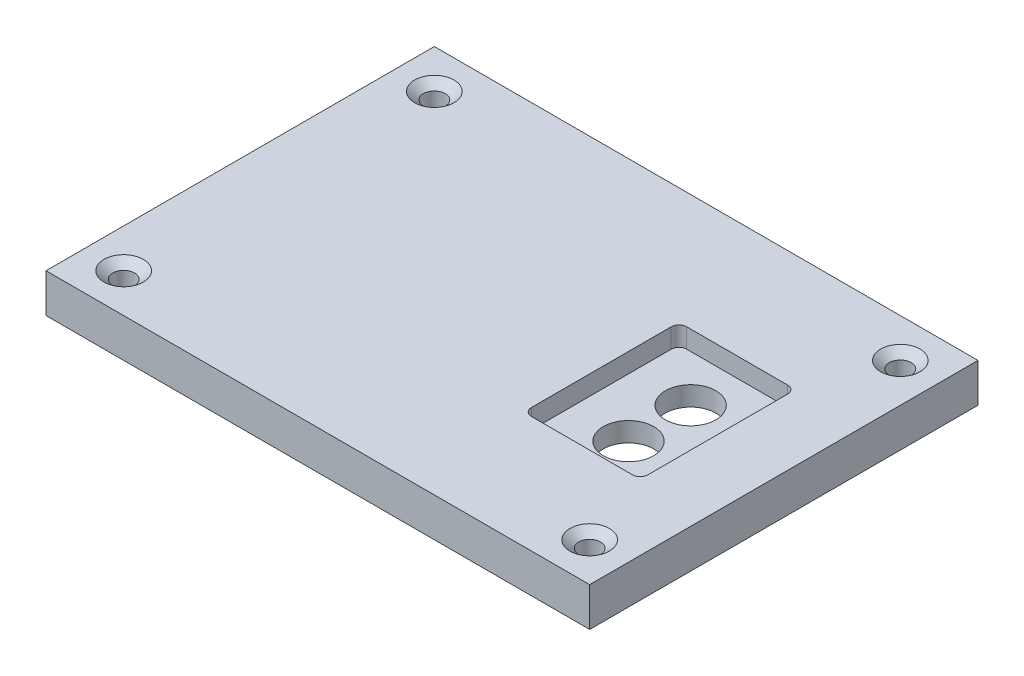
SolidWorks part; units mm, degrees
ref_plane "Front Plane" through (0, 0, 0) normal (0, 0, 1) x (1, 0, 0)
ref_plane "Top Plane" through (0, 0, 0) normal (0, 1, 0) x (1, 0, 0)
ref_plane "Right Plane" through (0, 0, 0) normal (1, 0, 0) x (0, 0, -1)
sketch "Sketch1" plane through (0, 0, 0) normal (0, 1, 0) x (1, 0, 0)
  line L1 (-88.9, -63.5) -> (88.9, -63.5)
  line L2 (-88.9, -63.5) -> (-88.9, 63.5)
  line L3 (-88.9, 63.5) -> (88.9, 63.5)
  line L4 (88.9, -63.5) -> (88.9, 63.5)
  line L5 (-88.9, -63.5) -> (88.9, 63.5) construction
  line L6 (-88.9, 63.5) -> (88.9, -63.5) construction
  point P0 (0, 0)
  dimension "D1" = 177.8
  dimension "D2" = 127
extrude "Boss-Extrude1" add sketch "Sketch1" along normal blind 12.7
sketch "Sketch2" plane through (0, 12.7, 0) normal (0, 1, 0) x (1, 0, 0)
  line L0 (-88.9, -63.5) -> (88.9, -63.5) construction
  line L1 (-88.9, 63.5) -> (-88.9, -63.5) construction
  line L2 (88.9, -63.5) -> (88.9, 63.5) construction
  line L3 (88.9, 63.5) -> (-88.9, 63.5) construction
  point P0 (76.2, 50.8)
  point P1 (76.2, -50.8)
  point P2 (-76.2, -50.8)
  point P11 (-76.2, 50.8)
  dimension "D1" = 12.7
  dimension "D2" = 12.7
  dimension "D3" = 12.7
  dimension "D4" = 12.7
hole_wizard "CSK for 1/4 Flat Head Machine Screw (100)1" positions "Sketch3" profile "Sketch5" countersink size "1/4" standard "ANSI Inch" end condition up to next
sketch "Sketch3" plane through (0, 12.7, 0) normal (0, 1, 0) x (1, 0, 0)
  point P0 (-76.2, -50.8)
  point P4 (76.2, -50.8)
  point P7 (76.2, 50.8)
  point P10 (-76.2, 50.8)
sketch "Sketch5" plane through (-76.2, 12.7, 50.8) normal (1, 0, 0) x (0, 0, 1)
  line L0 (0, 0) -> (0, 12.7)
  line L1 (0, 12.7) -> (3.5712, 12.7)
  line L2 (3.5712, 12.7) -> (3.5712, 2.4063)
  line L3 (3.5712, 2.4063) -> (6.4389, 0)
  line L5 (6.4389, 0) -> (0, 0)
  line L6 (-3.5712, 2.4063) -> (-6.4389, 0) construction
  line L11 (0, -6.35) -> (0, 107.95) construction
  dimension "Thru Hole Dia." = 7.1425
  dimension "Thru Hole Depth" = 12.7
  dimension "Near C'Sink Dia." = 12.8778
  dimension "Near C'Sink Angle" = 100
sketch "Sketch6" plane through (0, 12.7, 0) normal (0, 1, 0) x (1, 0, 0)
  line L0 (88.9, -63.5) -> (88.9, 63.5) construction
  line L2 (29.21, 25.4) -> (67.31, 25.4)
  line L3 (29.21, 25.4) -> (29.21, -25.4)
  line L4 (29.21, -25.4) -> (67.31, -25.4)
  line L5 (67.31, 25.4) -> (67.31, -25.4)
  line L6 (29.21, 25.4) -> (67.31, -25.4) construction
  line L7 (29.21, -25.4) -> (67.31, 25.4) construction
  point P0 (48.26, 0)
  point P3 (48.26, 0)
  dimension "D1" = 40.64
  dimension "D2" = 50.8
  dimension "D3" = 38.1
extrude "Cut-Extrude1" cut sketch "Sketch6" against normal blind 6.35 contours L5 L4 L3 L2
sketch "Sketch7" plane through (0, 6.35, 0) normal (0, 1, 0) x (1, 0, 0)
  line L0 (29.21, 25.4) -> (29.21, -25.4) construction
  circle A0 centre (48.26, -10.16) radius 8.255
  point P0 (48.26, -10.16)
  point P1 (48.26, 10.16)
  point P6 (29.21, 0)
  dimension "D4" = 16.51
  dimension "D1" = 20.32
  dimension "D2" = 10.16
  dimension "D3" = 19.05
sketch "Sketch8" plane through (0, 6.35, 0) normal (0, 1, 0) x (1, 0, 0)
  circle A0 centre (48.26, 10.16) radius 8.255
  dimension "D4" = 16.51
extrude "Cut-Extrude2" cut sketch "Sketch8" against normal up to next
extrude "Cut-Extrude3" cut sketch "Sketch7" against normal up to next contours A0
fillet "Fillet1" radius 2.54 4 edges at (67.31, 9.525, 25.4) (29.21, 9.525, 25.4) (29.21, 9.525, -25.4) (67.31, 9.525, -25.4)
